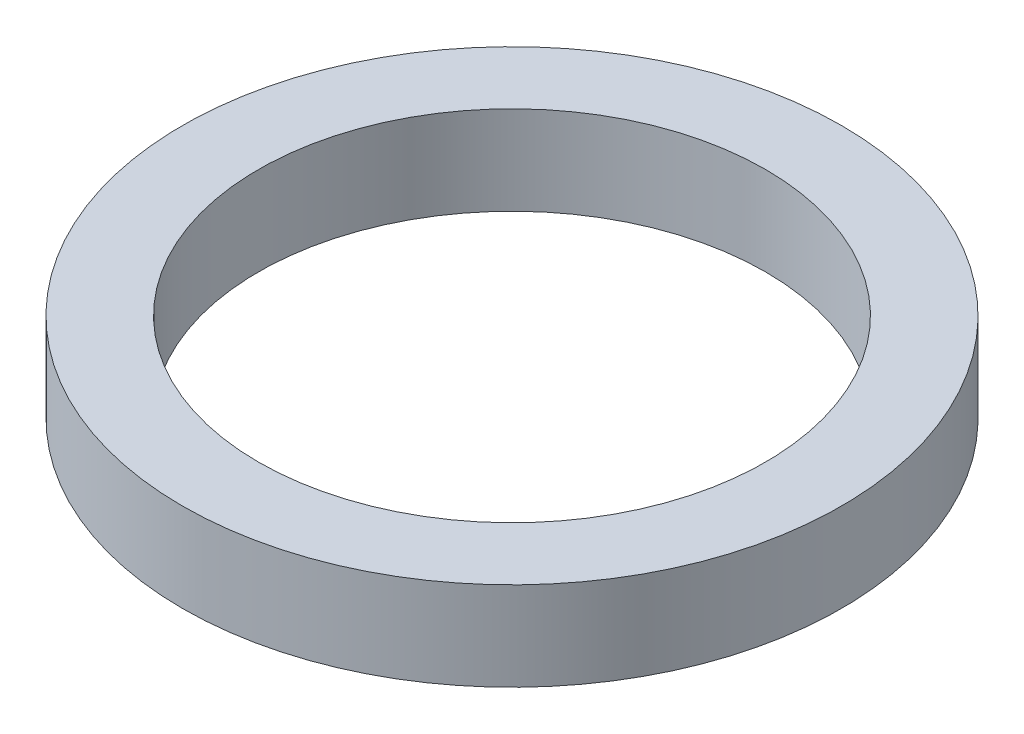
SolidWorks part; units mm, degrees
material "Литая легированная сталь"
ref_plane "Спереди" through (0, 0, 0) normal (0, 0, 1) x (1, 0, 0)
ref_plane "Сверху" through (0, 0, 0) normal (0, 1, 0) x (1, 0, 0)
ref_plane "Справа" through (0, 0, 0) normal (1, 0, 0) x (0, 0, -1)
sketch "Эскиз1" plane through (0, 0, 0) normal (0, 1, 0) x (1, 0, 0)
  circle A0 centre (0, 0) radius 20
  circle A1 centre (0, 0) radius 26
  dimension "D1" = 40
  dimension "D2" = 52
extrude "Бобышка-Вытянуть1" add sketch "Эскиз1" along normal blind 7
